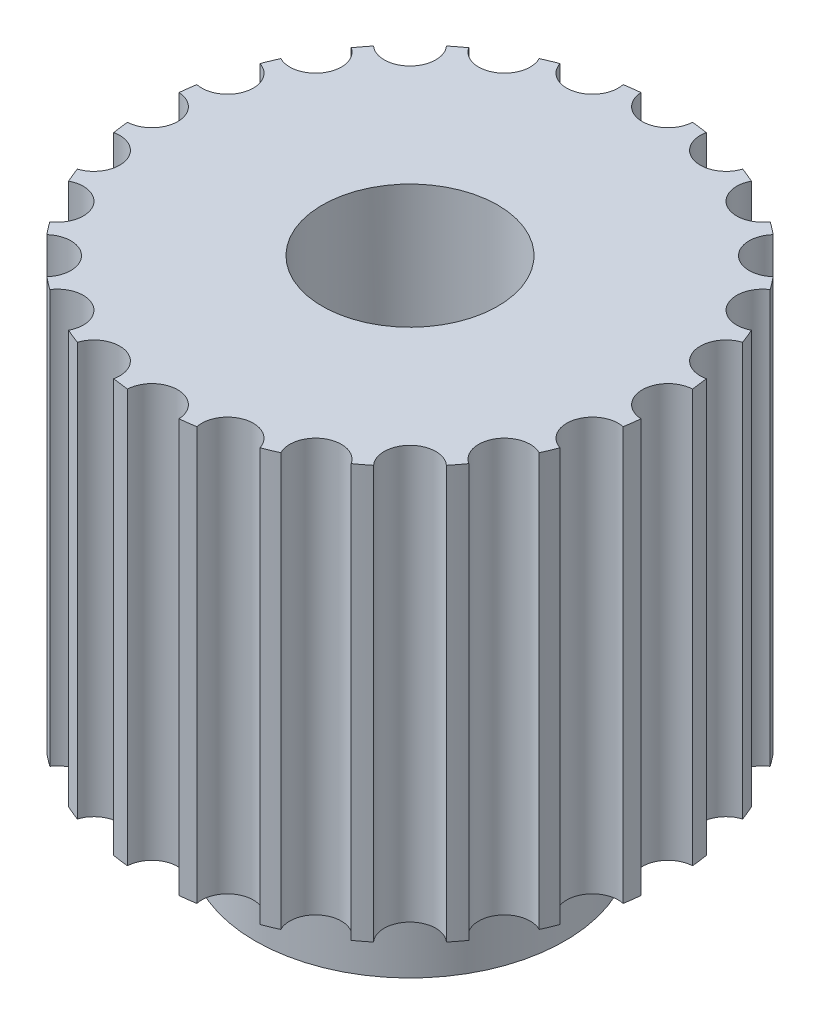
SolidWorks part; units mm, degrees
ref_plane "Front Plane" through (0, 0, 0) normal (0, 0, 1) x (1, 0, 0)
ref_plane "Top Plane" through (0, 0, 0) normal (0, 1, 0) x (1, 0, 0)
ref_plane "Right Plane" through (0, 0, 0) normal (1, 0, 0) x (0, 0, -1)
sketch "Sketch2" plane through (0, 0, 0) normal (0, 0, 1) x (1, 0, 0)
  line L0 (0, -5) -> (0, 5)
  line L1 (-3, -5) -> (3, -5)
  line L2 (-3, -5) -> (-3, 5)
  line L3 (-3, 5) -> (3, 5)
  line L4 (3, -5) -> (3, 5)
  line L5 (-3, -5) -> (3, 5) construction
  line L6 (-3, 5) -> (3, -5) construction
  line L7 (-5, -3) -> (5, -3)
  line L8 (-5, -3) -> (-5, 5)
  line L9 (-5, 5) -> (5, 5)
  line L10 (5, -3) -> (5, 5)
  line L11 (-5, -3) -> (5, 5) construction
  line L12 (-5, 5) -> (5, -3) construction
  line L13 (-1.7, -5) -> (1.7, -5)
  line L14 (-1.7, -5) -> (-1.7, 5)
  line L15 (-1.7, 5) -> (1.7, 5)
  line L16 (1.7, -5) -> (1.7, 5)
  line L17 (-1.7, -5) -> (1.7, 5) construction
  line L18 (-1.7, 5) -> (1.7, -5) construction
  point P0 (0, 0)
  point P6 (0, 1)
  point P13 (0, 0)
  dimension "D1" = 6
  dimension "D2" = 8
  dimension "D3" = 2
  dimension "D4" = 10
  dimension "D5" = 3.4
revolve "Revolve2" add sketch "Sketch2" angle 360 about L0
sketch "Sketch3" plane through (0, 0, 0) normal (1, 0, 0) x (0, 0, -1)
  line L0 (-5, -3) -> (5, 5) construction
  circle A0 centre (0, 1) radius 3
  dimension "D1" = 6
extrude "Cut-Extrude2" cut sketch "Sketch3" against normal blind 2 from offset 3 offset against normal yes
hole_wizard "M3x0.5 Tapped Hole1" positions "Sketch4" profile "Sketch5" tap size "M3x0.5" standard "ANSI Metric"
sketch "Sketch4" plane through (-3, 0, 0) normal (-1, 0, 0) x (0, 0, 1)
  circle A2 centre (0, 1) radius 3
  circle A3 centre (0, 1) radius 3
  point P5 (0, 1)
  dimension "D1" = 0
cosmetic thread "Hole Thread1" parameters "D1"=2.08, "D2"=3
sketch "Sketch5" plane through (-3, 1, 0) normal (0, 1, 0) x (0, 0, 1)
  line L0 (0, 0) -> (0, 3.7511)
  line L1 (0, 3.7511) -> (1.25, 3)
  line L2 (1.25, 3) -> (1.25, 0)
  line L5 (1.25, 0) -> (0, 0)
  line L10 (0, 3.7511) -> (-1.25, 3) construction
  line L11 (0, -6.35) -> (0, 107.95) construction
  dimension "Tap Drill Dia." = 2.5
  dimension "Tap Drill Depth" = 3
  dimension "Drill Angle" = 118
sketch "Sketch6" plane through (0, 5, 0) normal (0, 1, 0) x (1, 0, 0)
  line L0 (0, 0) -> (0, 5)
  circle A0 centre (0, 0) radius 5 construction
  circle A1 centre (0, 5) radius 0.5
  circle M1 centre (0, 0) radius 5
  dimension "D1" = 1
extrude "Cut-Extrude3" cut sketch "Sketch6" against normal through all contours A1 L0 M1 | L0 A1 M1
pattern_circular "CirPattern1" count 24 every 15 about axis through (0, 0, 0) along (0, 1, 0) of "Cut-Extrude3"
